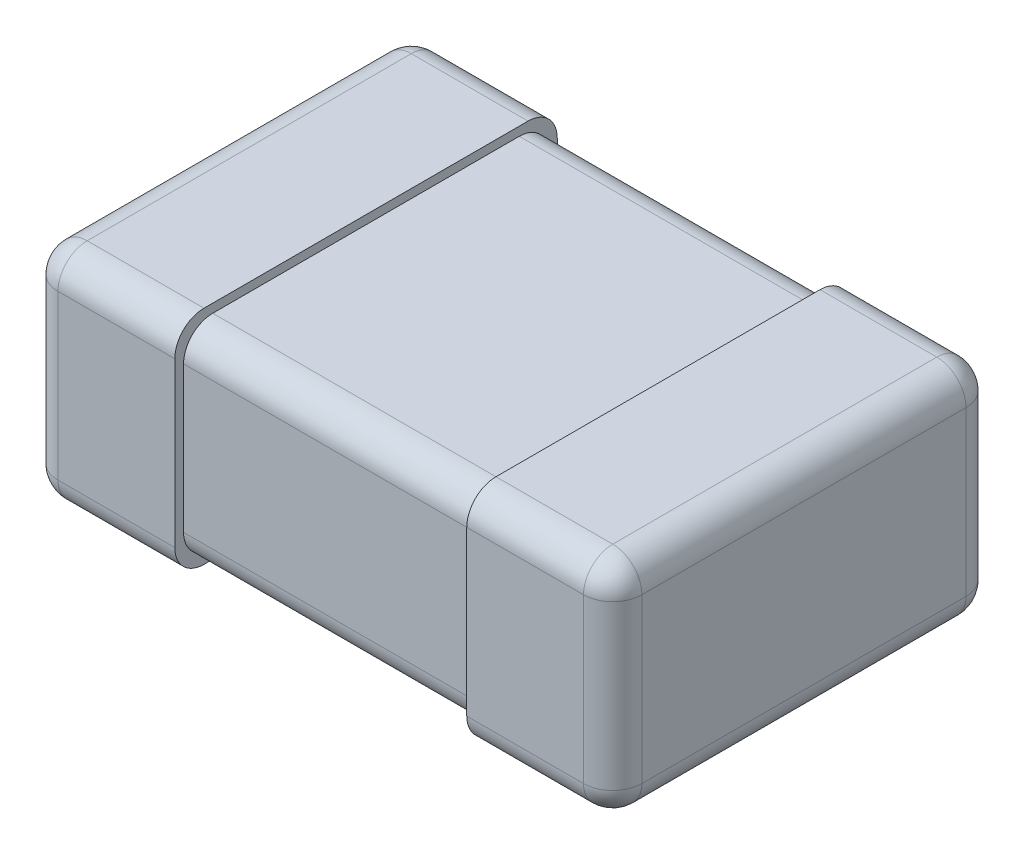
SolidWorks part; units mm, degrees
ref_plane "Front Plane" through (0, 0, 0) normal (0, 0, 1) x (1, 0, 0)
ref_plane "Top Plane" through (0, 0, 0) normal (0, 1, 0) x (1, 0, 0)
ref_plane "Right Plane" through (0, 0, 0) normal (1, 0, 0) x (0, 0, -1)
sketch "Sketch1" plane through (0, 0, 0) normal (0, 1, 0) x (1, 0, 0)
  line L1 (-1, 0.625) -> (1, 0.625)
  line L2 (-1, 0.625) -> (-1, -0.625)
  line L3 (-1, -0.625) -> (1, -0.625)
  line L4 (1, 0.625) -> (1, -0.625)
  point P4 (0, 0.625)
  point P6 (1, 0)
  dimension "D1" = 1.25
  dimension "D2" = 2
extrude "Extrude1" add sketch "Sketch1" along normal blind 0.7
sketch "Sketch2" plane through (0, 0, 0) normal (0, 0, 1) x (1, 0, 0)
  line L0 (-1, 0.7) -> (-1, 0) construction
  line L1 (-0.5, 0.73) -> (-1, 0.73)
  line L2 (-0.5, 0.73) -> (-0.5, -0.03)
  line L3 (-0.5, -0.03) -> (-1, -0.03)
  line L4 (-1, 0.73) -> (-1, -0.03)
  line L5 (-1, 0.7) -> (1, 0.7) construction
  line L6 (-1, 0) -> (1, 0) construction
  line L7 (0, 0) -> (0, -0.3575) construction
  line L8 (1, 0.73) -> (1, -0.03)
  line L9 (0.5, -0.03) -> (1, -0.03)
  line L10 (0.5, 0.73) -> (0.5, -0.03)
  line L11 (0.5, 0.73) -> (1, 0.73)
  dimension "D1" = 0.5
  dimension "D2" = 0.03
  dimension "D3" = 0.03
extrude "Extrude2" add sketch "Sketch2" along normal offset from surface 0.03 and the other way offset from surface (0.655 mm away) 0.03 up to face at (0, 0.35, 0.625) offset beyond the face yes other way up to face at (0, 0.35, -0.625)
ref_plane "Plane1" through (0, -0.03, 0) normal (0, 1, 0) x (-1, 0, 0)
sketch "Component_Outline" plane through (0, -0.03, 0) normal (0, 1, 0) x (-1, 0, 0)
  line L1 (-1, -0.655) -> (1, -0.655)
  line L2 (-1, -0.655) -> (-1, 0.655)
  line L3 (-1, 0.655) -> (1, 0.655)
  line L4 (1, -0.655) -> (1, 0.655)
fillet "Fillet1" radius 0.1 20 edges at (-1, 0.35, -0.655) (-1, 0.73, 0) (-1, 0.35, 0.655) (-1, -0.03, 0) (1, 0.35, -0.655) (1, -0.03, 0) (1, 0.35, 0.655) (1, 0.73, 0) (0, 0, 0.625) (0, 0.7, 0.625) (0, 0, -0.625) (0, 0.7, -0.625) (-0.75, -0.03, 0.655) (-0.75, 0.73, 0.655) (-0.75, -0.03, -0.655) (-0.75, 0.73, -0.655) (0.75, -0.03, -0.655) (0.75, -0.03, 0.655) (0.75, 0.73, -0.655) (0.75, 0.73, 0.655)
